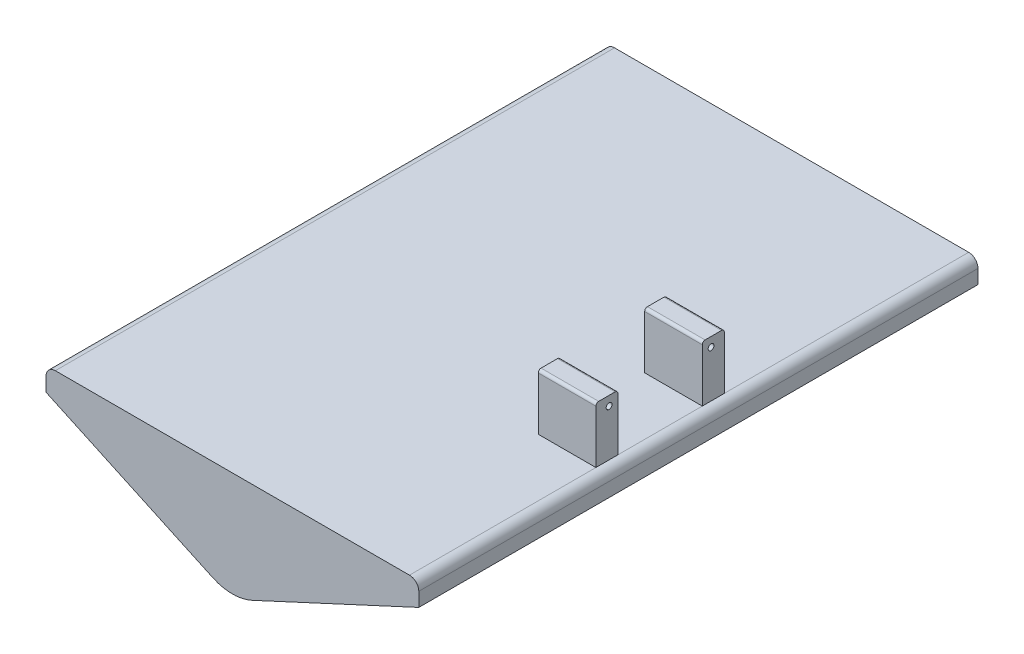
SolidWorks part; units mm, degrees
ref_plane "Front Plane" through (0, 0, 0) normal (0, 0, 1) x (1, 0, 0)
ref_plane "Top Plane" through (0, 0, 0) normal (0, 1, 0) x (1, 0, 0)
ref_plane "Right Plane" through (0, 0, 0) normal (1, 0, 0) x (0, 0, -1)
sketch "Sketch2" plane through (0, 0, 0) normal (0, 0, 1) x (1, 0, 0)
  line L0 (-50.8, -3.175) -> (-5.3359, -24.2247)
  line L1 (-50.8, 3.175) -> (50.8, 3.175)
  line L2 (-50.8, 3.175) -> (-50.8, -3.175)
  line L3 (-50.8, -3.175) -> (50.8, -3.175)
  line L4 (50.8, 3.175) -> (50.8, -3.175)
  line L5 (-50.8, 3.175) -> (50.8, -3.175) construction
  line L6 (-50.8, -3.175) -> (50.8, 3.175) construction
  line L7 (50.8, -3.175) -> (5.3359, -24.2247)
  arc A0 (-5.3359, -24.2247) -> (5.3359, -24.2247) centre (0, -12.7) ccw
  point P0 (0, 0)
  dimension "D3" = 25.4
  dimension "D1" = 101.6
  dimension "D2" = 6.35
  dimension "D4" = 12.7
extrude "Boss-Extrude1" add sketch "Sketch2" along normal blind 152.4 contours L0 A0 L7 L3 | L4 L1 L2 L3
sketch "Sketch3" plane through (0, 0, 152.4) normal (0, 0, 1) x (1, 0, 0)
  arc A0 (-5.3359, -24.2247) -> (5.3359, -24.2247) centre (0, -12.7) ccw construction
  arc A1 (-5.3359, -24.2247) -> (5.3359, -24.2247) centre (0, -12.7) ccw
  circle A2 centre (0, -12.7) radius 6.985
  dimension "D1" = 13.97
extrude "Cut-Extrude1" cut sketch "Sketch3" against normal through all from offset 6.35 contours A2 offset against normal yes
sketch "Sketch4" plane through (0, 3.175, 0) normal (0, 1, 0) x (1, 0, 0)
  line L0 (-50.8, -152.4) -> (-50.8, 0) construction
  line L1 (-50.8, -57.15) -> (50.8, -57.15)
  line L2 (-50.8, -57.15) -> (-50.8, -95.25)
  line L3 (-50.8, -95.25) -> (50.8, -95.25)
  line L4 (50.8, -57.15) -> (50.8, -95.25)
  line L5 (50.8, -152.4) -> (50.8, 0) construction
  line L6 (0, 0) -> (0, -152.4) construction
  line L7 (-50.8, 0) -> (50.8, 0) construction
  line L8 (-50.8, -152.4) -> (50.8, -152.4) construction
  line L9 (50.8, -76.2) -> (-50.8, -76.2) construction
  point P16 (0, -76.2)
  dimension "D1" = 38.1
extrude "Cut-Extrude2" cut sketch "Sketch4" against normal through all from offset 6.35 offset against normal yes
fillet "Fillet4" radius 2.54 2 edges at (-50.8, 3.175, 76.2) (50.8, 3.175, 76.2)
sketch "Sketch5" plane through (0, 3.175, 0) normal (0, 1, 0) x (1, 0, 0)
  line L0 (48.26, -152.4) -> (48.26, 0) construction
  line L1 (48.26, -95.6) -> (32.56, -95.6)
  line L2 (48.26, -95.6) -> (48.26, -101.6)
  line L3 (48.26, -101.6) -> (32.56, -101.6)
  line L4 (32.56, -95.6) -> (32.56, -101.6)
  line L5 (48.26, -66.6) -> (32.56, -66.6)
  line L6 (48.26, -66.6) -> (48.26, -72.6)
  line L7 (48.26, -72.6) -> (32.56, -72.6)
  line L8 (32.56, -66.6) -> (32.56, -72.6)
  line L9 (-48.26, -152.4) -> (48.26, -152.4) construction
  point P10 (0, 0)
  point P11 (0, 0)
  point P12 (32.56, -60.7149)
  point P13 (0, 0)
  dimension "D1" = 15.7
  dimension "D2" = 6
  dimension "D3" = 15.7
  dimension "D4" = 6
  dimension "D5" = 23
  dimension "D6" = 50.8
extrude "Boss-Extrude2" add sketch "Sketch5" along normal blind 15.24
sketch "Sketch6" plane through (32.56, 0, 0) normal (-1, 0, 0) x (0, 0, 1)
  line L0 (95.6, 18.415) -> (95.6, 3.175) construction
  line L2 (95.6, 3.175) -> (101.6, 3.175) construction
  line L3 (72.6, 10.795) -> (95.6, 10.795) construction
  line L4 (72.6, 18.415) -> (72.6, 3.175) construction
  line L5 (84.1, 10.795) -> (84.1, 3.175) construction
  line L6 (0, 3.175) -> (152.4, 3.175) construction
  circle A0 centre (97.995, 15.875) radius 0.8
  circle A1 centre (70.205, 15.875) radius 0.8
  dimension "D1" = 1.6
  dimension "D2" = 12.7
  dimension "D3" = 2.395
extrude "Cut-Extrude4" cut sketch "Sketch6" against normal through all contours A1 | A0
fillet "Fillet7" radius 0.762 2 edges at (40.41, 18.415, 101.6) (40.41, 18.415, 95.6)
fillet "Fillet8" radius 0.762 2 edges at (40.41, 18.415, 66.6) (40.41, 18.415, 72.6)
sketch "Sketch18" plane through (32.56, 0, 0) normal (-1, 0, 0) x (0, 0, 1)
  point P0 (97.995, 15.875)
  point P3 (70.205, 15.875)
hole_wizard "Tap Drill for M2 Tap3" positions "Sketch18" profile "Sketch19" hole size "M2" standard "ISO" end condition through all
sketch "Sketch19" plane through (32.56, 15.875, 97.995) normal (0, 1, 0) x (0, 0, 1)
  line L0 (0, 0) -> (0, 18.24)
  line L1 (0, 18.24) -> (0.8, 18.24)
  line L2 (0.8, 18.24) -> (0.8, 0)
  line L5 (0.8, 0) -> (0, 0)
  line L11 (0, -6.35) -> (0, 107.95) construction
  dimension "Thru Hole Dia." = 1.6
  dimension "Thru Hole Depth" = 18.24
